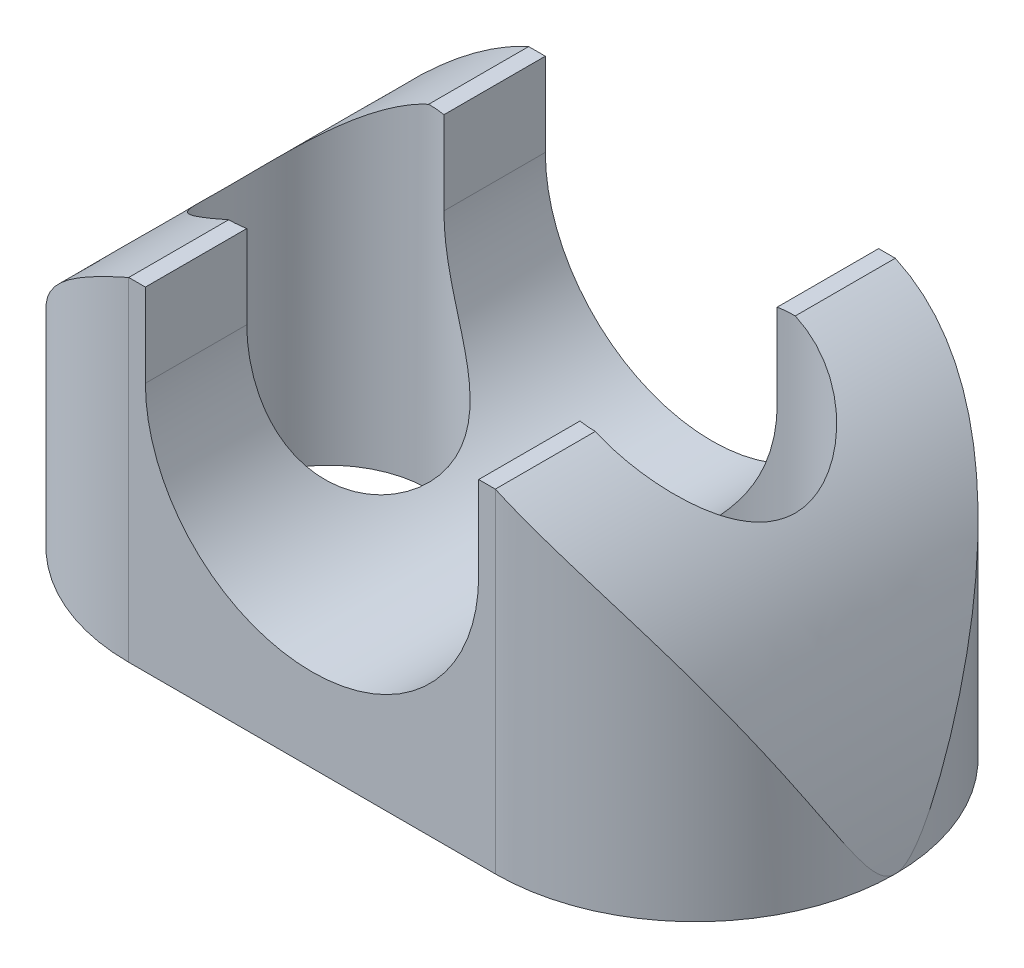
SolidWorks part; units mm, degrees
material "AISI 1020"
ref_plane "Plano frontal" through (0, 0, 0) normal (0, 0, 1) x (1, 0, 0)
ref_plane "Plano superior" through (0, 0, 0) normal (0, 1, 0) x (1, 0, 0)
ref_plane "Plano direito" through (0, 0, 0) normal (1, 0, 0) x (0, 0, -1)
sketch "Esboço1" plane through (0, 0, 0) normal (0, 1, 0) x (1, 0, 0)
  line L0 (-5.5, 0) -> (5.5, 0) construction
  line L1 (-11.5, 0) -> (11.5, 0) construction
  line L2 (-5.5, -6) -> (5.5, -6)
  line L3 (-5.5, 6) -> (5.5, 6)
  circle A0 centre (-5.5, 0) radius 3
  circle A1 centre (5.5, 0) radius 3
  arc A2 (5.5, -6) -> (5.5, 6) centre (5.5, 0) ccw
  arc A3 (-5.5, 6) -> (-5.5, -6) centre (-5.5, 0) ccw
  point P4 (0, 0)
  point P9 (0, 0)
  dimension "D2" = 6
  dimension "D3" = 23
  dimension "D1" = 11
extrude "Ressalto-extrusão1" add sketch "Esboço1" along normal blind 10
sketch "Esboço2" plane through (0, 0, 6) normal (0, 0, 1) x (1, 0, 0)
  line L0 (0, 10) -> (0, 7.5) construction
  line L1 (-5.5, 10) -> (5.5, 10) construction
  line L2 (-5, 7.5) -> (-5, 10)
  line L3 (5, 7.5) -> (5, 10)
  line L4 (-5, 10) -> (5, 10)
  arc A0 (-5, 7.5) -> (5, 7.5) centre (0, 7.5) ccw
  dimension "D1" = 10
  dimension "D2" = 2.5
extrude "Corte-extrusão1" cut sketch "Esboço2" against normal through all
sketch "Esboço3" plane through (0, 0, 6) normal (0, 0, 1) x (1, 0, 0)
  line L8 (-5.5, 10) -> (-5.5, 0) construction
  line L10 (-11.5, 0) -> (-11.5, 10)
  line L11 (-11.5, 10) -> (11.5, 10)
  line L12 (11.5, 0) -> (11.5, 10)
  spline S0 degree 2 poles (-11.5, 0) (-10.8906, 7.573) (-5.5, 10) knots 0 0 0 0.339761 0.339761 0.339761
  spline S1 degree 2 poles (5.5, 10) (10.8906, 7.573) (11.5, 0) knots 0.660239 0.660239 0.660239 1 1 1
extrude "Corte-extrusão2" cut sketch "Esboço3" against normal through all contours L10 S0 L11 | L11 S1 L12
